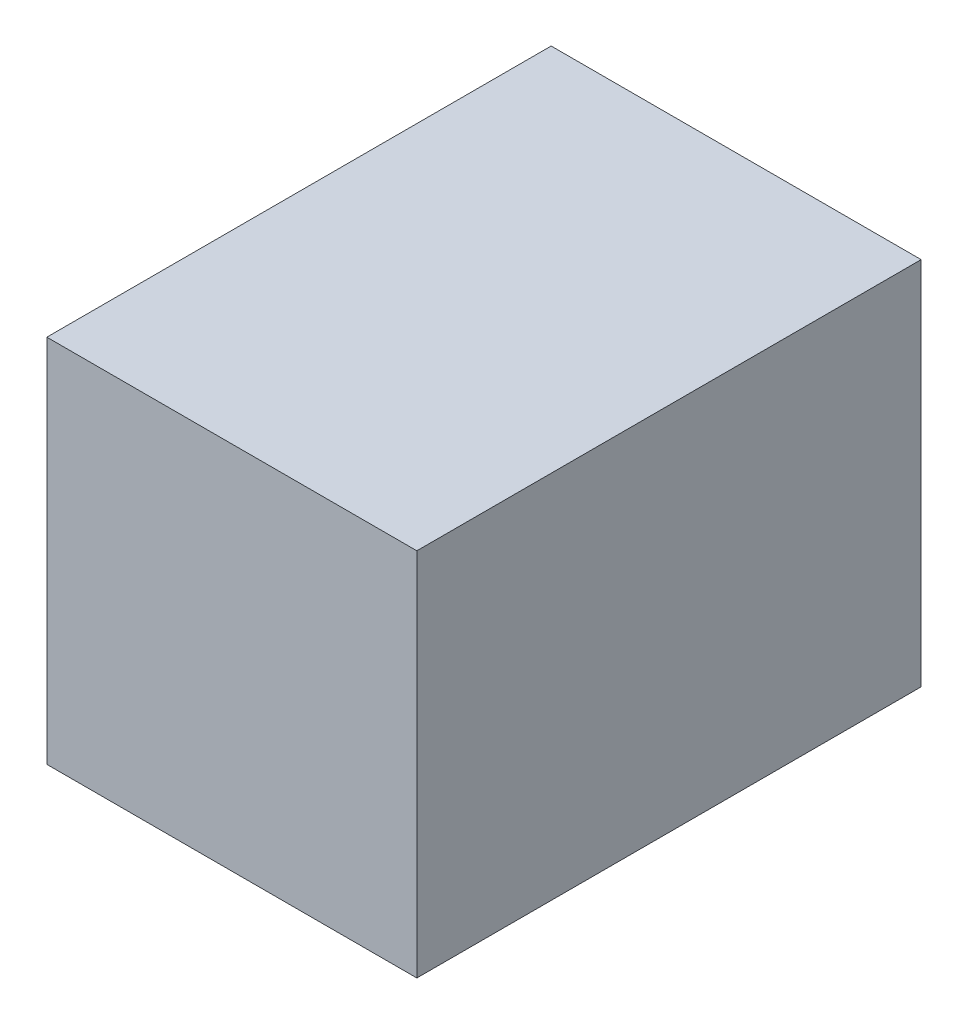
SolidWorks part; units mm, degrees
ref_plane "Front Plane" through (0, 0, 0) normal (0, 0, 1) x (1, 0, 0)
ref_plane "Top Plane" through (0, 0, 0) normal (0, 1, 0) x (1, 0, 0)
ref_plane "Right Plane" through (0, 0, 0) normal (1, 0, 0) x (0, 0, -1)
sketch "Sketch1" plane through (0, 0, 0) normal (0, 0, 1) x (1, 0, 0)
  line L1 (-28.65, 28.65) -> (28.65, 28.65)
  line L2 (-28.65, 28.65) -> (-28.65, -28.65)
  line L3 (-28.65, -28.65) -> (28.65, -28.65)
  line L4 (28.65, 28.65) -> (28.65, -28.65)
  line L5 (-28.65, 28.65) -> (28.65, -28.65) construction
  line L6 (-28.65, -28.65) -> (28.65, 28.65) construction
  point P0 (0, 0)
  dimension "D1" = 57.3
  dimension "D2" = 57.3
extrude "Boss-Extrude1" add sketch "Sketch1" along normal blind 78.1
sketch "Sketch2" plane through (0, 0, 0) normal (0, 0, -1) x (-1, 0, 0)
  circle A0 centre (0, 0) radius 3.175
  dimension "D1" = 6.35
extrude "Cut-Extrude1" cut sketch "Sketch2" against normal blind 10
